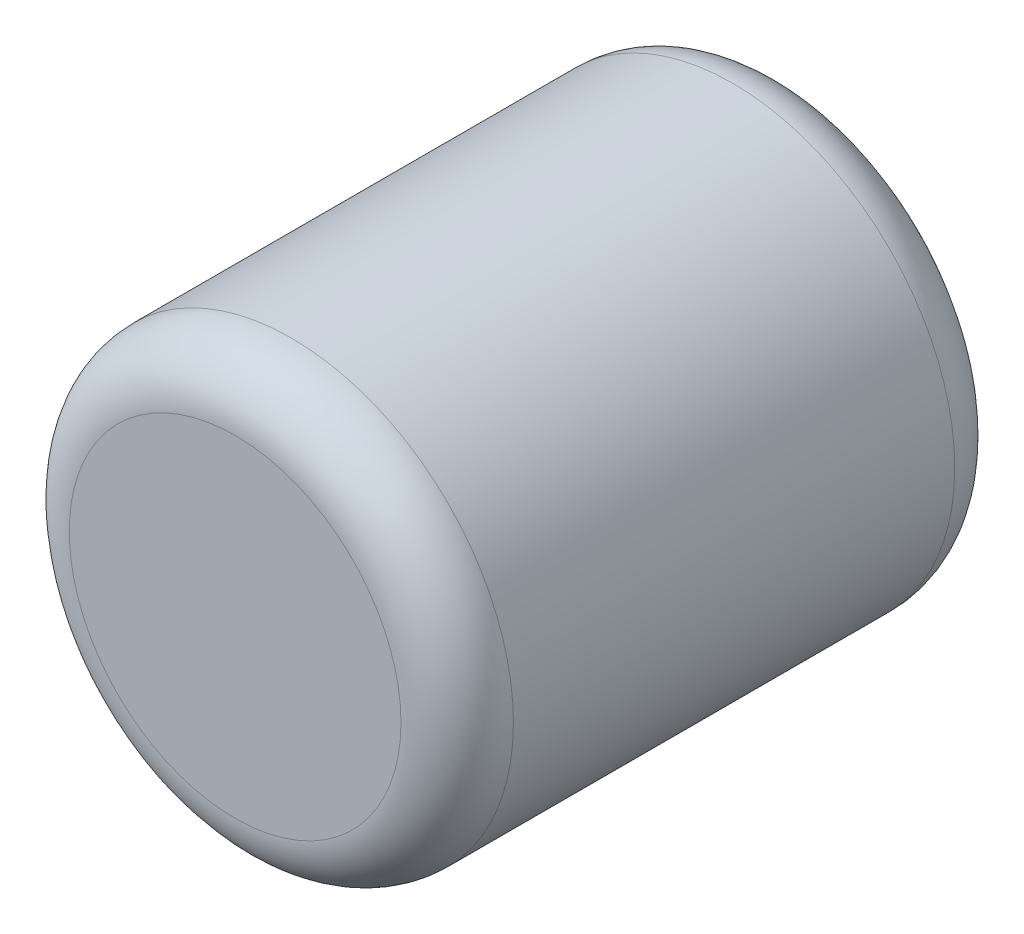
SolidWorks part; units mm, degrees
ref_plane "Alzado" through (0, 0, 0) normal (0, 0, 1) x (1, 0, 0)
ref_plane "Planta" through (0, 0, 0) normal (0, 1, 0) x (1, 0, 0)
ref_plane "Vista lateral" through (0, 0, 0) normal (1, 0, 0) x (0, 0, -1)
sketch "Croquis1" plane through (0, 0, 0) normal (0, 0, 1) x (1, 0, 0)
  circle A0 centre (0, 0) radius 3.95
  dimension "D1" = 7.9
extrude "Saliente-Extruir1" add sketch "Croquis1" along normal blind 9.85
fillet "Redondeo1" radius 1 2 edges at (3.95, 0, 9.85) (3.95, 0, 0)
